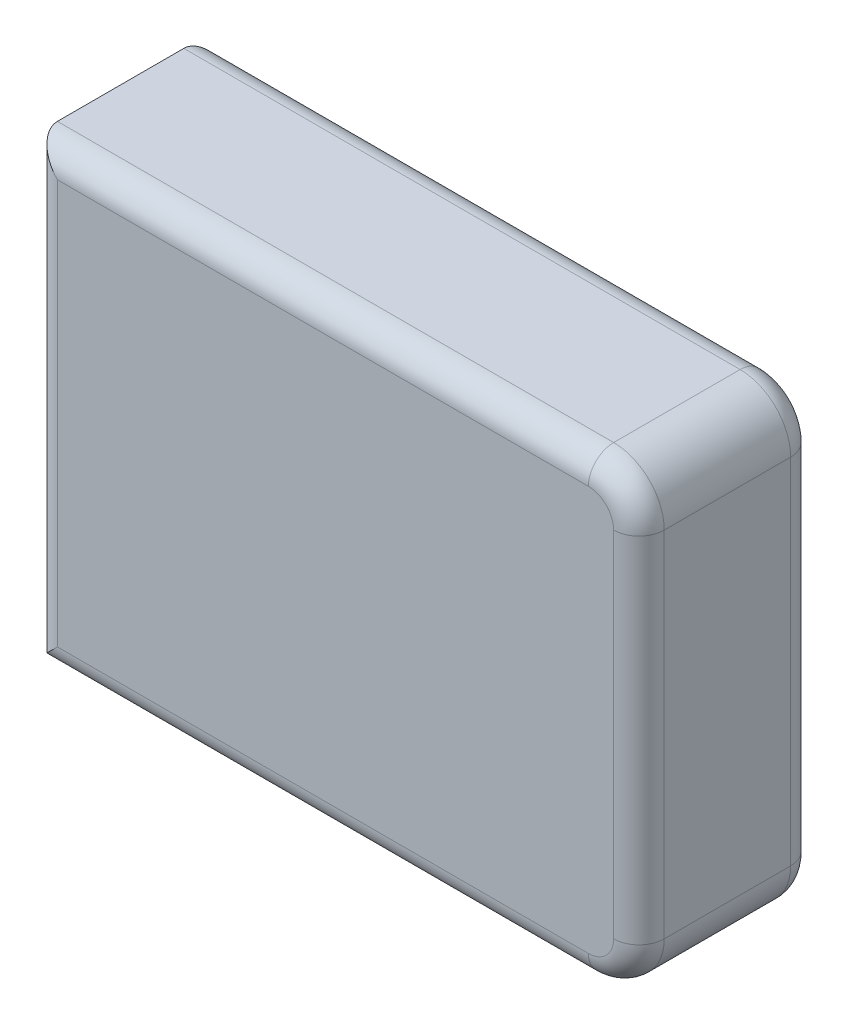
SolidWorks part; units mm, degrees
ref_plane "Front Plane" through (0, 0, 0) normal (0, 0, 1) x (1, 0, 0)
ref_plane "Top Plane" through (0, 0, 0) normal (0, 1, 0) x (1, 0, 0)
ref_plane "Right Plane" through (0, 0, 0) normal (1, 0, 0) x (0, 0, -1)
sketch "Sketch1" plane through (0, 0, 0) normal (0, 0, 1) x (1, 0, 0)
  line L1 (-60, 45) -> (60, 45)
  line L2 (-60, 45) -> (-60, -45)
  line L3 (-60, -45) -> (60, -45)
  line L4 (60, 45) -> (60, -45)
  line L5 (-60, 45) -> (60, -45) construction
  line L6 (-60, -45) -> (60, 45) construction
  point P0 (0, 0)
  dimension "D1" = 120
  dimension "D2" = 90
extrude "Boss-Extrude1" add sketch "Sketch1" along normal blind 35
fillet "Fillet1" radius 10 2 edges at (60, -45, 17.5) (60, 45, 17.5)
fillet "Fillet2" radius 5 12 edges at (57.0711, 42.0711, 0) (57.0711, -42.0711, 0) (57.0711, -42.0711, 35) (57.0711, 42.0711, 35) (-60, 0, 0) (-5, 45, 0) (60, 0, 0) (-5, -45, 0) (-5, 45, 35) (-60, 0, 35) (-5, -45, 35) (60, 0, 35)
